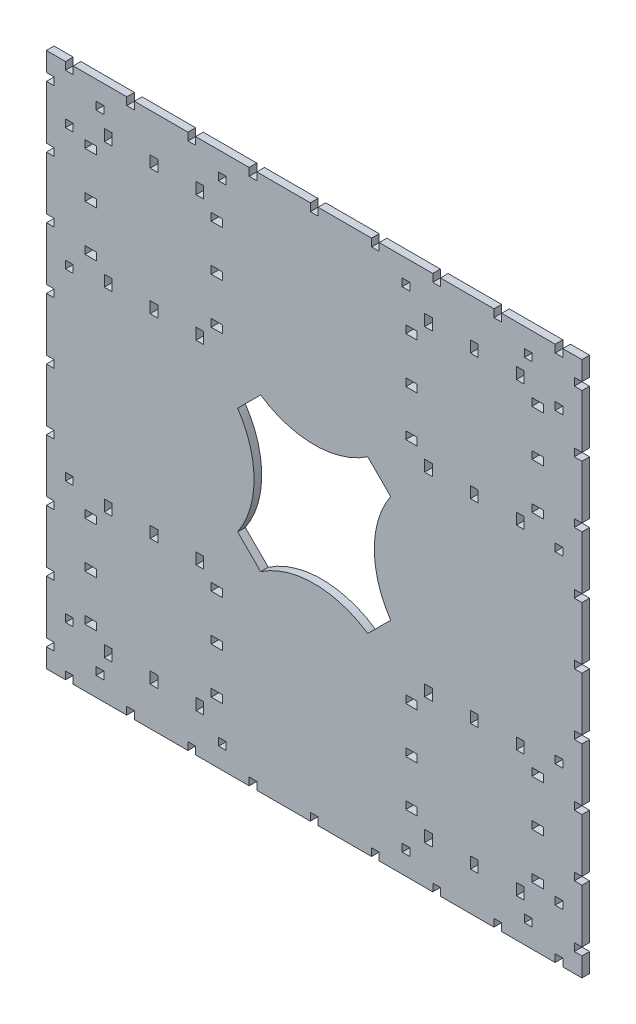
SolidWorks part; units mm, degrees
ref_plane "Front Plane" through (0, 0, 0) normal (0, 0, 1) x (1, 0, 0)
ref_plane "Top Plane" through (0, 0, 0) normal (0, 1, 0) x (1, 0, 0)
ref_plane "Right Plane" through (0, 0, 0) normal (1, 0, 0) x (0, 0, -1)
sketch "Sketch1" plane through (0, 0, 0) normal (0, 0, 1) x (1, 0, 0)
  line L1284 (46.6944, 22.6404) -> (43.6944, 22.6404)
  line L1285 (43.6944, 22.6404) -> (43.6944, 18.1292)
  line L1286 (43.6944, 18.1292) -> (46.6944, 18.1292)
  line L1287 (46.6944, 18.1292) -> (46.6944, 22.6404)
  line L1288 (28.6944, 22.6404) -> (25.6944, 22.6404)
  line L1289 (25.6944, 22.6404) -> (25.6944, 18.1292)
  line L1290 (25.6944, 18.1292) -> (28.6944, 18.1292)
  line L1291 (28.6944, 18.1292) -> (28.6944, 22.6404)
  line L1292 (193.3596, 64.6944) -> (193.3596, 61.6944)
  line L1293 (193.3596, 61.6944) -> (197.8708, 61.6944)
  line L1294 (197.8708, 61.6944) -> (197.8708, 64.6944)
  line L1295 (197.8708, 64.6944) -> (193.3596, 64.6944)
  line L1296 (169.3056, 193.3596) -> (172.3056, 193.3596)
  line L1297 (172.3056, 193.3596) -> (172.3056, 197.8708)
  line L1298 (172.3056, 197.8708) -> (169.3056, 197.8708)
  line L1299 (169.3056, 197.8708) -> (169.3056, 193.3596)
  line L1300 (187.3056, 193.3596) -> (190.3056, 193.3596)
  line L1301 (190.3056, 193.3596) -> (190.3056, 197.8708)
  line L1302 (190.3056, 197.8708) -> (187.3056, 197.8708)
  line L1303 (187.3056, 197.8708) -> (187.3056, 193.3596)
  line L1304 (169.3056, 18.1292) -> (169.3056, 22.6404)
  line L1305 (169.3056, 22.6404) -> (172.3056, 22.6404)
  line L1306 (172.3056, 22.6404) -> (172.3056, 18.1292)
  line L1307 (172.3056, 18.1292) -> (169.3056, 18.1292)
  line L1308 (151.3056, 18.1292) -> (151.3056, 22.6404)
  line L1309 (151.3056, 22.6404) -> (154.3056, 22.6404)
  line L1310 (154.3056, 22.6404) -> (154.3056, 18.1292)
  line L1311 (154.3056, 18.1292) -> (151.3056, 18.1292)
  line L1312 (187.3056, 18.1292) -> (187.3056, 22.6404)
  line L1313 (187.3056, 22.6404) -> (190.3056, 22.6404)
  line L1314 (190.3056, 22.6404) -> (190.3056, 18.1292)
  line L1315 (190.3056, 18.1292) -> (187.3056, 18.1292)
  line L1316 (197.8708, 169.3056) -> (193.3596, 169.3056)
  line L1317 (193.3596, 169.3056) -> (193.3596, 172.3056)
  line L1318 (193.3596, 172.3056) -> (197.8708, 172.3056)
  line L1319 (197.8708, 172.3056) -> (197.8708, 169.3056)
  line L1320 (197.8708, 151.3056) -> (193.3596, 151.3056)
  line L1321 (193.3596, 151.3056) -> (193.3596, 154.3056)
  line L1322 (193.3596, 154.3056) -> (197.8708, 154.3056)
  line L1323 (197.8708, 154.3056) -> (197.8708, 151.3056)
  line L1324 (197.8708, 187.3056) -> (193.3596, 187.3056)
  line L1325 (193.3596, 187.3056) -> (193.3596, 190.3056)
  line L1326 (193.3596, 190.3056) -> (197.8708, 190.3056)
  line L1327 (197.8708, 190.3056) -> (197.8708, 187.3056)
  line L1328 (46.6944, 197.8708) -> (46.6944, 193.3596)
  line L1329 (46.6944, 193.3596) -> (43.6944, 193.3596)
  line L1330 (43.6944, 193.3596) -> (43.6944, 197.8708)
  line L1331 (43.6944, 197.8708) -> (46.6944, 197.8708)
  line L1332 (64.6944, 197.8708) -> (64.6944, 193.3596)
  line L1333 (64.6944, 193.3596) -> (61.6944, 193.3596)
  line L1334 (61.6944, 193.3596) -> (61.6944, 197.8708)
  line L1335 (61.6944, 197.8708) -> (64.6944, 197.8708)
  line L1336 (28.6944, 197.8708) -> (28.6944, 193.3596)
  line L1337 (28.6944, 193.3596) -> (25.6944, 193.3596)
  line L1338 (25.6944, 193.3596) -> (25.6944, 197.8708)
  line L1339 (25.6944, 197.8708) -> (28.6944, 197.8708)
  line L1340 (22.6404, 151.3056) -> (22.6404, 154.3056)
  line L1341 (22.6404, 154.3056) -> (18.1292, 154.3056)
  line L1342 (18.1292, 154.3056) -> (18.1292, 151.3056)
  line L1343 (18.1292, 151.3056) -> (22.6404, 151.3056)
  line L1344 (73.5, 202.5) -> (73.5, 205.5)
  line L1345 (73.5, 205.5) -> (70.5, 205.5)
  line L1346 (70.5, 205.5) -> (70.5, 202.5)
  line L1347 (70.5, 202.5) -> (73.5, 202.5)
  line L1348 (193.5, 202.5) -> (193.5, 205.5)
  line L1349 (193.5, 205.5) -> (190.5, 205.5)
  line L1350 (190.5, 205.5) -> (190.5, 202.5)
  line L1351 (190.5, 202.5) -> (193.5, 202.5)
  line L1352 (25.5, 202.5) -> (25.5, 205.5)
  line L1353 (25.5, 205.5) -> (22.5, 205.5)
  line L1354 (22.5, 205.5) -> (22.5, 202.5)
  line L1355 (22.5, 202.5) -> (25.5, 202.5)
  line L1356 (145.5, 202.5) -> (145.5, 205.5)
  line L1357 (145.5, 205.5) -> (142.5, 205.5)
  line L1358 (142.5, 205.5) -> (142.5, 202.5)
  line L1359 (142.5, 202.5) -> (145.5, 202.5)
  line L1360 (202.5, 142.5) -> (205.5, 142.5)
  line L1361 (205.5, 142.5) -> (205.5, 145.5)
  line L1362 (205.5, 145.5) -> (202.5, 145.5)
  line L1363 (202.5, 145.5) -> (202.5, 142.5)
  line L1364 (142.5, 13.5) -> (142.5, 10.5)
  line L1365 (142.5, 10.5) -> (145.5, 10.5)
  line L1366 (145.5, 10.5) -> (145.5, 13.5)
  line L1367 (145.5, 13.5) -> (142.5, 13.5)
  line L1368 (13.5, 73.5) -> (10.5, 73.5)
  line L1369 (10.5, 73.5) -> (10.5, 70.5)
  line L1370 (10.5, 70.5) -> (13.5, 70.5)
  line L1371 (13.5, 70.5) -> (13.5, 73.5)
  line L1372 (202.5, 190.5) -> (205.5, 190.5)
  line L1373 (205.5, 190.5) -> (205.5, 193.5)
  line L1374 (205.5, 193.5) -> (202.5, 193.5)
  line L1375 (202.5, 193.5) -> (202.5, 190.5)
  line L1376 (190.5, 13.5) -> (190.5, 10.5)
  line L1377 (190.5, 10.5) -> (193.5, 10.5)
  line L1378 (193.5, 10.5) -> (193.5, 13.5)
  line L1379 (193.5, 13.5) -> (190.5, 13.5)
  line L1380 (13.5, 25.5) -> (10.5, 25.5)
  line L1381 (10.5, 25.5) -> (10.5, 22.5)
  line L1382 (10.5, 22.5) -> (13.5, 22.5)
  line L1383 (13.5, 22.5) -> (13.5, 25.5)
  line L1384 (202.5, 22.5) -> (205.5, 22.5)
  line L1385 (205.5, 22.5) -> (205.5, 25.5)
  line L1386 (205.5, 25.5) -> (202.5, 25.5)
  line L1387 (202.5, 25.5) -> (202.5, 22.5)
  line L1388 (22.5, 13.5) -> (22.5, 10.5)
  line L1389 (22.5, 10.5) -> (25.5, 10.5)
  line L1390 (25.5, 10.5) -> (25.5, 13.5)
  line L1391 (25.5, 13.5) -> (22.5, 13.5)
  line L1392 (13.5, 193.5) -> (10.5, 193.5)
  line L1393 (10.5, 193.5) -> (10.5, 190.5)
  line L1394 (10.5, 190.5) -> (13.5, 190.5)
  line L1395 (13.5, 190.5) -> (13.5, 193.5)
  line L1396 (202.5, 70.5) -> (205.5, 70.5)
  line L1397 (205.5, 70.5) -> (205.5, 73.5)
  line L1398 (205.5, 73.5) -> (202.5, 73.5)
  line L1399 (202.5, 73.5) -> (202.5, 70.5)
  line L1400 (70.5, 13.5) -> (70.5, 10.5)
  line L1401 (70.5, 10.5) -> (73.5, 10.5)
  line L1402 (73.5, 10.5) -> (73.5, 13.5)
  line L1403 (73.5, 13.5) -> (70.5, 13.5)
  line L1404 (13.5, 145.5) -> (10.5, 145.5)
  line L1405 (10.5, 145.5) -> (10.5, 142.5)
  line L1406 (10.5, 142.5) -> (13.5, 142.5)
  line L1407 (13.5, 142.5) -> (13.5, 145.5)
  line L1408 (18.1292, 28.6944) -> (22.6404, 28.6944)
  line L1409 (22.6404, 28.6944) -> (22.6404, 25.6944)
  line L1410 (22.6404, 25.6944) -> (18.1292, 25.6944)
  line L1411 (18.1292, 25.6944) -> (18.1292, 28.6944)
  line L1412 (18.1292, 64.6944) -> (22.6404, 64.6944)
  line L1413 (22.6404, 64.6944) -> (22.6404, 61.6944)
  line L1414 (22.6404, 61.6944) -> (18.1292, 61.6944)
  line L1415 (18.1292, 61.6944) -> (18.1292, 64.6944)
  line L1416 (18.1292, 46.6944) -> (22.6404, 46.6944)
  line L1417 (22.6404, 46.6944) -> (22.6404, 43.6944)
  line L1418 (22.6404, 43.6944) -> (18.1292, 43.6944)
  line L1419 (18.1292, 43.6944) -> (18.1292, 46.6944)
  line L1420 (22.6404, 187.3056) -> (22.6404, 190.3056)
  line L1421 (22.6404, 190.3056) -> (18.1292, 190.3056)
  line L1422 (18.1292, 190.3056) -> (18.1292, 187.3056)
  line L1423 (18.1292, 187.3056) -> (22.6404, 187.3056)
  line L1424 (22.6404, 169.3056) -> (22.6404, 172.3056)
  line L1425 (22.6404, 172.3056) -> (18.1292, 172.3056)
  line L1426 (18.1292, 172.3056) -> (18.1292, 169.3056)
  line L1427 (18.1292, 169.3056) -> (22.6404, 169.3056)
  line L1428 (151.3056, 193.3596) -> (154.3056, 193.3596)
  line L1429 (154.3056, 193.3596) -> (154.3056, 197.8708)
  line L1430 (154.3056, 197.8708) -> (151.3056, 197.8708)
  line L1431 (151.3056, 197.8708) -> (151.3056, 193.3596)
  line L1432 (193.3596, 28.6944) -> (193.3596, 25.6944)
  line L1433 (193.3596, 25.6944) -> (197.8708, 25.6944)
  line L1434 (197.8708, 25.6944) -> (197.8708, 28.6944)
  line L1435 (197.8708, 28.6944) -> (193.3596, 28.6944)
  line L1436 (193.3596, 46.6944) -> (193.3596, 43.6944)
  line L1437 (193.3596, 43.6944) -> (197.8708, 43.6944)
  line L1438 (197.8708, 43.6944) -> (197.8708, 46.6944)
  line L1439 (197.8708, 46.6944) -> (193.3596, 46.6944)
  line L1440 (64.6944, 22.6404) -> (61.6944, 22.6404)
  line L1441 (61.6944, 22.6404) -> (61.6944, 18.1292)
  line L1442 (61.6944, 18.1292) -> (64.6944, 18.1292)
  line L1443 (64.6944, 18.1292) -> (64.6944, 22.6404)
  line L1444 (28.6944, 143.938) -> (25.6944, 143.938)
  line L1445 (25.6944, 143.938) -> (25.6944, 148.3708)
  line L1446 (25.6944, 148.3708) -> (28.6944, 148.3708)
  line L1447 (28.6944, 148.3708) -> (28.6944, 143.938)
  line L1448 (46.6944, 143.938) -> (43.6944, 143.938)
  line L1449 (43.6944, 143.938) -> (43.6944, 148.3708)
  line L1450 (43.6944, 148.3708) -> (46.6944, 148.3708)
  line L1451 (46.6944, 148.3708) -> (46.6944, 143.938)
  line L1452 (64.6944, 143.938) -> (61.6944, 143.938)
  line L1453 (61.6944, 143.938) -> (61.6944, 148.3708)
  line L1454 (61.6944, 148.3708) -> (64.6944, 148.3708)
  line L1455 (64.6944, 148.3708) -> (64.6944, 143.938)
  line L1456 (72.062, 154.3056) -> (72.062, 151.3056)
  line L1457 (72.062, 151.3056) -> (67.6292, 151.3056)
  line L1458 (67.6292, 151.3056) -> (67.6292, 154.3056)
  line L1459 (67.6292, 154.3056) -> (72.062, 154.3056)
  line L1460 (72.062, 190.3056) -> (72.062, 187.3056)
  line L1461 (72.062, 187.3056) -> (67.6292, 187.3056)
  line L1462 (67.6292, 187.3056) -> (67.6292, 190.3056)
  line L1463 (67.6292, 190.3056) -> (72.062, 190.3056)
  line L1464 (72.062, 172.3056) -> (72.062, 169.3056)
  line L1465 (72.062, 169.3056) -> (67.6292, 169.3056)
  line L1466 (67.6292, 169.3056) -> (67.6292, 172.3056)
  line L1467 (67.6292, 172.3056) -> (72.062, 172.3056)
  line L1468 (143.938, 187.3056) -> (143.938, 190.3056)
  line L1469 (143.938, 190.3056) -> (148.3708, 190.3056)
  line L1470 (148.3708, 190.3056) -> (148.3708, 187.3056)
  line L1471 (148.3708, 187.3056) -> (143.938, 187.3056)
  line L1472 (143.938, 169.3056) -> (143.938, 172.3056)
  line L1473 (143.938, 172.3056) -> (148.3708, 172.3056)
  line L1474 (148.3708, 172.3056) -> (148.3708, 169.3056)
  line L1475 (148.3708, 169.3056) -> (143.938, 169.3056)
  line L1476 (143.938, 151.3056) -> (143.938, 154.3056)
  line L1477 (143.938, 154.3056) -> (148.3708, 154.3056)
  line L1478 (148.3708, 154.3056) -> (148.3708, 151.3056)
  line L1479 (148.3708, 151.3056) -> (143.938, 151.3056)
  line L1480 (187.3056, 72.062) -> (190.3056, 72.062)
  line L1481 (190.3056, 72.062) -> (190.3056, 67.6292)
  line L1482 (190.3056, 67.6292) -> (187.3056, 67.6292)
  line L1483 (187.3056, 67.6292) -> (187.3056, 72.062)
  line L1484 (169.3056, 72.062) -> (172.3056, 72.062)
  line L1485 (172.3056, 72.062) -> (172.3056, 67.6292)
  line L1486 (172.3056, 67.6292) -> (169.3056, 67.6292)
  line L1487 (169.3056, 67.6292) -> (169.3056, 72.062)
  line L1488 (151.3056, 72.062) -> (154.3056, 72.062)
  line L1489 (154.3056, 72.062) -> (154.3056, 67.6292)
  line L1490 (154.3056, 67.6292) -> (151.3056, 67.6292)
  line L1491 (151.3056, 67.6292) -> (151.3056, 72.062)
  line L1492 (72.062, 28.6944) -> (72.062, 25.6944)
  line L1493 (72.062, 25.6944) -> (67.6292, 25.6944)
  line L1494 (67.6292, 25.6944) -> (67.6292, 28.6944)
  line L1495 (67.6292, 28.6944) -> (72.062, 28.6944)
  line L1496 (72.062, 46.6944) -> (72.062, 43.6944)
  line L1497 (72.062, 43.6944) -> (67.6292, 43.6944)
  line L1498 (67.6292, 43.6944) -> (67.6292, 46.6944)
  line L1499 (67.6292, 46.6944) -> (72.062, 46.6944)
  line L1500 (72.062, 64.6944) -> (72.062, 61.6944)
  line L1501 (72.062, 61.6944) -> (67.6292, 61.6944)
  line L1502 (67.6292, 61.6944) -> (67.6292, 64.6944)
  line L1503 (67.6292, 64.6944) -> (72.062, 64.6944)
  line L1504 (154.3056, 143.938) -> (151.3056, 143.938)
  line L1505 (151.3056, 143.938) -> (151.3056, 148.3708)
  line L1506 (151.3056, 148.3708) -> (154.3056, 148.3708)
  line L1507 (154.3056, 148.3708) -> (154.3056, 143.938)
  line L1508 (190.3056, 143.938) -> (187.3056, 143.938)
  line L1509 (187.3056, 143.938) -> (187.3056, 148.3708)
  line L1510 (187.3056, 148.3708) -> (190.3056, 148.3708)
  line L1511 (190.3056, 148.3708) -> (190.3056, 143.938)
  line L1512 (172.3056, 143.938) -> (169.3056, 143.938)
  line L1513 (169.3056, 143.938) -> (169.3056, 148.3708)
  line L1514 (169.3056, 148.3708) -> (172.3056, 148.3708)
  line L1515 (172.3056, 148.3708) -> (172.3056, 143.938)
  line L1516 (143.938, 61.6944) -> (143.938, 64.6944)
  line L1517 (143.938, 64.6944) -> (148.3708, 64.6944)
  line L1518 (148.3708, 64.6944) -> (148.3708, 61.6944)
  line L1519 (148.3708, 61.6944) -> (143.938, 61.6944)
  line L1520 (143.938, 25.6944) -> (143.938, 28.6944)
  line L1521 (143.938, 28.6944) -> (148.3708, 28.6944)
  line L1522 (148.3708, 28.6944) -> (148.3708, 25.6944)
  line L1523 (148.3708, 25.6944) -> (143.938, 25.6944)
  line L1524 (143.938, 43.6944) -> (143.938, 46.6944)
  line L1525 (143.938, 46.6944) -> (148.3708, 46.6944)
  line L1526 (148.3708, 46.6944) -> (148.3708, 43.6944)
  line L1527 (148.3708, 43.6944) -> (143.938, 43.6944)
  line L1528 (61.6944, 72.062) -> (64.6944, 72.062)
  line L1529 (64.6944, 72.062) -> (64.6944, 67.6292)
  line L1530 (64.6944, 67.6292) -> (61.6944, 67.6292)
  line L1531 (61.6944, 67.6292) -> (61.6944, 72.062)
  line L1532 (25.6944, 72.062) -> (28.6944, 72.062)
  line L1533 (28.6944, 72.062) -> (28.6944, 67.6292)
  line L1534 (28.6944, 67.6292) -> (25.6944, 67.6292)
  line L1535 (25.6944, 67.6292) -> (25.6944, 72.062)
  line L1536 (43.6944, 72.062) -> (46.6944, 72.062)
  line L1537 (46.6944, 72.062) -> (46.6944, 67.6292)
  line L1538 (46.6944, 67.6292) -> (43.6944, 67.6292)
  line L1539 (43.6944, 67.6292) -> (43.6944, 72.062)
  line L1540 (138, 87) -> (129, 78)
  line L1541 (87, 78) -> (78, 87)
  line L1542 (78, 129) -> (87, 138)
  line L1543 (129, 138) -> (138, 129)
  line L1544 (6, 202.5) -> (3, 202.5)
  line L1545 (3, 202.5) -> (3, 181.5)
  line L1546 (3, 181.5) -> (6, 181.5)
  line L1547 (6, 181.5) -> (6, 178.5)
  line L1548 (6, 178.5) -> (3, 178.5)
  line L1549 (3, 178.5) -> (3, 157.5)
  line L1550 (3, 157.5) -> (6, 157.5)
  line L1551 (6, 157.5) -> (6, 154.5)
  line L1552 (6, 154.5) -> (3, 154.5)
  line L1553 (3, 154.5) -> (3, 133.5)
  line L1554 (3, 133.5) -> (6, 133.5)
  line L1555 (6, 133.5) -> (6, 130.5)
  line L1556 (6, 130.5) -> (3, 130.5)
  line L1557 (3, 130.5) -> (3, 109.5)
  line L1558 (3, 109.5) -> (6, 109.5)
  line L1559 (6, 109.5) -> (6, 106.5)
  line L1560 (6, 106.5) -> (3, 106.5)
  line L1561 (3, 106.5) -> (3, 85.5)
  line L1562 (3, 85.5) -> (6, 85.5)
  line L1563 (6, 85.5) -> (6, 82.5)
  line L1564 (6, 82.5) -> (3, 82.5)
  line L1565 (3, 82.5) -> (3, 61.5)
  line L1566 (3, 61.5) -> (6, 61.5)
  line L1567 (6, 61.5) -> (6, 58.5)
  line L1568 (6, 58.5) -> (3, 58.5)
  line L1569 (3, 58.5) -> (3, 37.5)
  line L1570 (3, 37.5) -> (6, 37.5)
  line L1571 (6, 37.5) -> (6, 34.5)
  line L1572 (6, 34.5) -> (3, 34.5)
  line L1573 (3, 34.5) -> (3, 13.5)
  line L1574 (3, 13.5) -> (6, 13.5)
  line L1575 (6, 13.5) -> (6, 10.5)
  line L1576 (6, 10.5) -> (3, 10.5)
  line L1577 (3, 10.5) -> (3, 3)
  line L1578 (3, 3) -> (10.5, 3)
  line L1579 (10.5, 3) -> (10.5, 6)
  line L1580 (10.5, 6) -> (13.5, 6)
  line L1581 (13.5, 6) -> (13.5, 3)
  line L1582 (13.5, 3) -> (34.5, 3)
  line L1583 (34.5, 3) -> (34.5, 6)
  line L1584 (34.5, 6) -> (37.5, 6)
  line L1585 (37.5, 6) -> (37.5, 3)
  line L1586 (37.5, 3) -> (58.5, 3)
  line L1587 (58.5, 3) -> (58.5, 6)
  line L1588 (58.5, 6) -> (61.5, 6)
  line L1589 (61.5, 6) -> (61.5, 3)
  line L1590 (61.5, 3) -> (82.5, 3)
  line L1591 (82.5, 3) -> (82.5, 6)
  line L1592 (82.5, 6) -> (85.5, 6)
  line L1593 (85.5, 6) -> (85.5, 3)
  line L1594 (85.5, 3) -> (106.5, 3)
  line L1595 (106.5, 3) -> (106.5, 6)
  line L1596 (106.5, 6) -> (109.5, 6)
  line L1597 (109.5, 6) -> (109.5, 3)
  line L1598 (109.5, 3) -> (130.5, 3)
  line L1599 (130.5, 3) -> (130.5, 6)
  line L1600 (130.5, 6) -> (133.5, 6)
  line L1601 (133.5, 6) -> (133.5, 3)
  line L1602 (133.5, 3) -> (154.5, 3)
  line L1603 (154.5, 3) -> (154.5, 6)
  line L1604 (154.5, 6) -> (157.5, 6)
  line L1605 (157.5, 6) -> (157.5, 3)
  line L1606 (157.5, 3) -> (178.5, 3)
  line L1607 (178.5, 3) -> (178.5, 6)
  line L1608 (178.5, 6) -> (181.5, 6)
  line L1609 (181.5, 6) -> (181.5, 3)
  line L1610 (181.5, 3) -> (202.5, 3)
  line L1611 (202.5, 3) -> (202.5, 6)
  line L1612 (202.5, 6) -> (205.5, 6)
  line L1613 (205.5, 6) -> (205.5, 3)
  line L1614 (205.5, 3) -> (213, 3)
  line L1615 (213, 3) -> (213, 10.5)
  line L1616 (213, 10.5) -> (210, 10.5)
  line L1617 (210, 10.5) -> (210, 13.5)
  line L1618 (210, 13.5) -> (213, 13.5)
  line L1619 (213, 13.5) -> (213, 34.5)
  line L1620 (213, 34.5) -> (210, 34.5)
  line L1621 (210, 34.5) -> (210, 37.5)
  line L1622 (210, 37.5) -> (213, 37.5)
  line L1623 (213, 37.5) -> (213, 58.5)
  line L1624 (213, 58.5) -> (210, 58.5)
  line L1625 (210, 58.5) -> (210, 61.5)
  line L1626 (210, 61.5) -> (213, 61.5)
  line L1627 (213, 61.5) -> (213, 82.5)
  line L1628 (213, 82.5) -> (210, 82.5)
  line L1629 (210, 82.5) -> (210, 85.5)
  line L1630 (210, 85.5) -> (213, 85.5)
  line L1631 (213, 85.5) -> (213, 106.5)
  line L1632 (213, 106.5) -> (210, 106.5)
  line L1633 (210, 106.5) -> (210, 109.5)
  line L1634 (210, 109.5) -> (213, 109.5)
  line L1635 (213, 109.5) -> (213, 130.5)
  line L1636 (213, 130.5) -> (210, 130.5)
  line L1637 (210, 130.5) -> (210, 133.5)
  line L1638 (210, 133.5) -> (213, 133.5)
  line L1639 (213, 133.5) -> (213, 154.5)
  line L1640 (213, 154.5) -> (210, 154.5)
  line L1641 (210, 154.5) -> (210, 157.5)
  line L1642 (210, 157.5) -> (213, 157.5)
  line L1643 (213, 157.5) -> (213, 178.5)
  line L1644 (213, 178.5) -> (210, 178.5)
  line L1645 (210, 178.5) -> (210, 181.5)
  line L1646 (210, 181.5) -> (213, 181.5)
  line L1647 (213, 181.5) -> (213, 202.5)
  line L1648 (213, 202.5) -> (210, 202.5)
  line L1649 (210, 202.5) -> (210, 205.5)
  line L1650 (210, 205.5) -> (213, 205.5)
  line L1651 (213, 205.5) -> (213, 213)
  line L1652 (213, 213) -> (205.5, 213)
  line L1653 (205.5, 213) -> (205.5, 210)
  line L1654 (205.5, 210) -> (202.5, 210)
  line L1655 (202.5, 210) -> (202.5, 213)
  line L1656 (202.5, 213) -> (181.5, 213)
  line L1657 (181.5, 213) -> (181.5, 210)
  line L1658 (181.5, 210) -> (178.5, 210)
  line L1659 (178.5, 210) -> (178.5, 213)
  line L1660 (178.5, 213) -> (157.5, 213)
  line L1661 (157.5, 213) -> (157.5, 210)
  line L1662 (157.5, 210) -> (154.5, 210)
  line L1663 (154.5, 210) -> (154.5, 213)
  line L1664 (154.5, 213) -> (133.5, 213)
  line L1665 (133.5, 213) -> (133.5, 210)
  line L1666 (133.5, 210) -> (130.5, 210)
  line L1667 (130.5, 210) -> (130.5, 213)
  line L1668 (130.5, 213) -> (109.5, 213)
  line L1669 (109.5, 213) -> (109.5, 210)
  line L1670 (109.5, 210) -> (106.5, 210)
  line L1671 (106.5, 210) -> (106.5, 213)
  line L1672 (106.5, 213) -> (85.5, 213)
  line L1673 (85.5, 213) -> (85.5, 210)
  line L1674 (85.5, 210) -> (82.5, 210)
  line L1675 (82.5, 210) -> (82.5, 213)
  line L1676 (82.5, 213) -> (61.5, 213)
  line L1677 (61.5, 213) -> (61.5, 210)
  line L1678 (61.5, 210) -> (58.5, 210)
  line L1679 (58.5, 210) -> (58.5, 213)
  line L1680 (58.5, 213) -> (37.5, 213)
  line L1681 (37.5, 213) -> (37.5, 210)
  line L1682 (37.5, 210) -> (34.5, 210)
  line L1683 (34.5, 210) -> (34.5, 213)
  line L1684 (34.5, 213) -> (13.5, 213)
  line L1685 (13.5, 213) -> (13.5, 210)
  line L1686 (13.5, 210) -> (10.5, 210)
  line L1687 (10.5, 210) -> (10.5, 213)
  line L1688 (10.5, 213) -> (3, 213)
  line L1689 (3, 213) -> (3, 205.5)
  line L1690 (3, 205.5) -> (6, 205.5)
  line L1691 (6, 205.5) -> (6, 202.5)
  arc A0 (138, 129) -> (138, 87) centre (169.0685, 108) ccw
  arc A1 (129, 78) -> (87, 78) centre (108, 46.9315) ccw
  arc A2 (78, 87) -> (78, 129) centre (46.9315, 108) ccw
  arc A3 (87, 138) -> (129, 138) centre (108, 169.0685) ccw
extrude "Boss-Extrude1" add sketch "Sketch1" along normal blind 3
